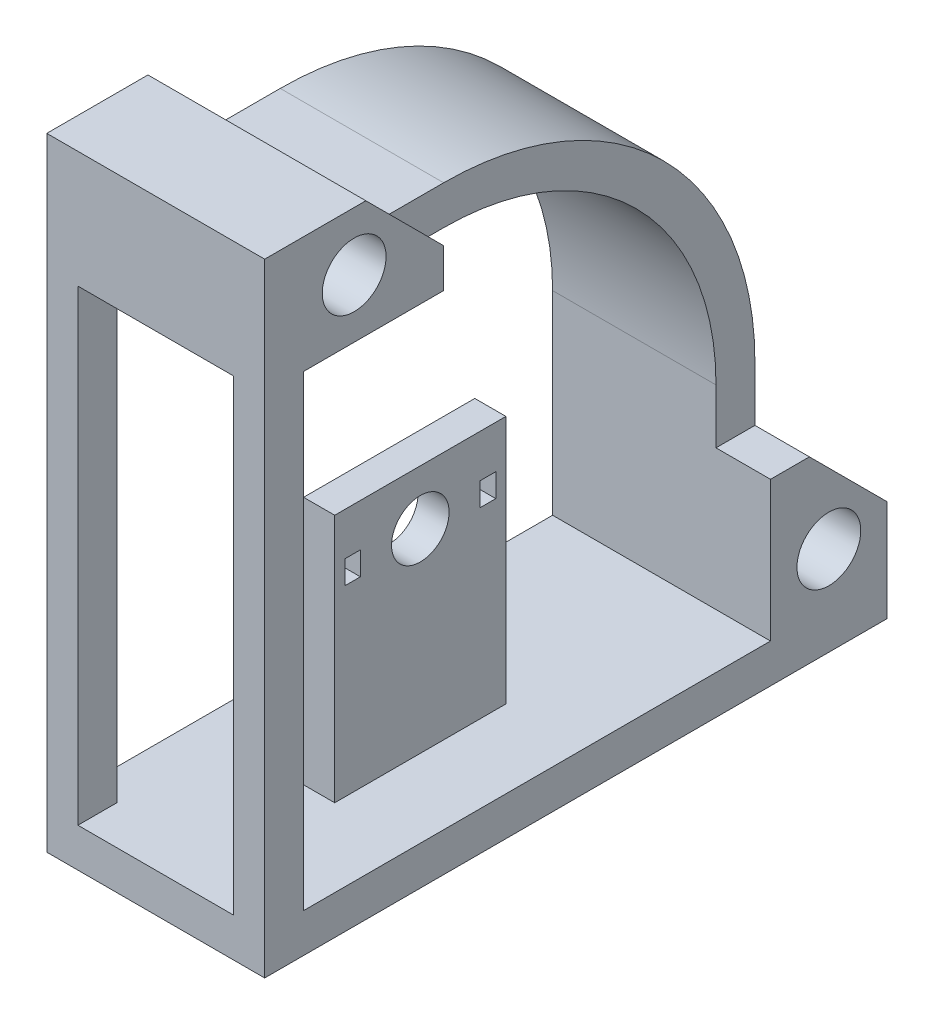
SolidWorks part; units mm, degrees
ref_plane "Спереди" through (0, 0, 0) normal (0, 0, 1) x (1, 0, 0)
ref_plane "Сверху" through (0, 0, 0) normal (0, 1, 0) x (1, 0, 0)
ref_plane "Справа" through (0, 0, 0) normal (1, 0, 0) x (0, 0, -1)
sketch "Sketch2" plane through (0, 0, 0) normal (1, 0, 0) x (0, 0, -1)
  line L0 (0, 40) -> (0, 0) construction
  line L1 (0, 0) -> (40, 0) construction
  line L2 (0, 40) -> (-30, 40)
  line L3 (40, -30) -> (-30, -30)
  line L4 (-25, 35) -> (-25, -25)
  line L5 (40, -30) -> (40, 0)
  line L6 (-30, -30) -> (-30, 40)
  line L7 (-25, -25) -> (35, -25)
  line L8 (35, -25) -> (35, 0)
  line L9 (-25, 35) -> (0, 35)
  line L10 (24.7487, 24.7487) -> (28.2843, 28.2843) construction
  line L12 (-25, 35) -> (-30, 35) construction
  line L13 (-25, -25) -> (-25, -30) construction
  arc A0 (0, 40) -> (40, 0) centre (0, 0) cw
  arc A1 (0, 35) -> (35, 0) centre (0, 0) cw
  dimension "D1" = 40
  dimension "D3" = 5
  dimension "D2" = 70
extrude "Boss-Extrude1" add sketch "Sketch2" along normal blind 28
sketch "Sketch3" plane through (28, 0, 0) normal (1, 0, 0) x (0, 0, -1)
  line L0 (-11, -25) -> (-11, 7)
  line L1 (-25, -25) -> (35, -25) construction
  line L2 (-11, 7) -> (11, 7)
  line L3 (11, 7) -> (11, -25)
  line L4 (11, -25) -> (-11, -25)
  line L5 (0, 7) -> (0, -25) construction
  line L6 (8.7, 0) -> (-8.7, 0) construction
  line L7 (7.7, 0) -> (3.7, 0) construction
  line L8 (-9.7, -1.5) -> (-7.7, -1.5)
  line L9 (-9.7, -1.5) -> (-9.7, 1.5)
  line L10 (-9.7, 1.5) -> (-7.7, 1.5)
  line L11 (-7.7, -1.5) -> (-7.7, 1.5)
  line L12 (-9.7, -1.5) -> (-7.7, 1.5) construction
  line L13 (-9.7, 1.5) -> (-7.7, -1.5) construction
  line L14 (9.7, -1.5) -> (7.7, -1.5)
  line L15 (9.7, -1.5) -> (9.7, 1.5)
  line L16 (9.7, 1.5) -> (7.7, 1.5)
  line L17 (7.7, -1.5) -> (7.7, 1.5)
  line L18 (9.7, -1.5) -> (7.7, 1.5) construction
  line L19 (9.7, 1.5) -> (7.7, -1.5) construction
  circle A3 centre (0, 0) radius 3.7
  point P18 (0, 0)
  dimension "D1" = 7.4
  dimension "D2" = 22
  dimension "D3" = 7
  dimension "D4" = 2
  dimension "D5" = 3
  dimension "D6" = 4
extrude "Boss-Extrude2" add sketch "Sketch3" against normal blind 4 from offset 10 offset against normal yes
sketch "Sketch4" plane through (28, 0, 0) normal (1, 0, 0) x (0, 0, -1)
  line L0 (0, 40) -> (-7, 40)
  line L1 (0, 40) -> (-30, 40) construction
  line L2 (-7, 40) -> (-7, 35)
  line L3 (0, 35) -> (-25, 35) construction
  line L4 (-7, 35) -> (0, 35)
  line L5 (35, -7) -> (40, -7)
  line L6 (35, -25) -> (35, 0) construction
  line L7 (40, -30) -> (40, 0) construction
  line L8 (40, -7) -> (40, 0)
  line L9 (35, 0) -> (35, -7)
  arc A0 (0, 40) -> (40, 0) centre (0, 0) cw
  arc A1 (35, 0) -> (0, 35) centre (0, 0) ccw
  arc A3 (40, 0) -> (0, 40) centre (0, 0) ccw construction
  dimension "D1" = 7
  dimension "D2" = 7
extrude "Cut-Extrude1" cut sketch "Sketch4" against normal blind 7
chamfer "Chamfer1" distance 10 angle 30 1 edges at (14, -25, 0)
sketch "Sketch5" plane through (0, 0, 30) normal (0, 0, 1) x (1, 0, 0)
  line L0 (14, 40) -> (14, -30) construction
  line L1 (28, 40) -> (0, 40) construction
  line L2 (28, -30) -> (0, -30) construction
  line L4 (24, -25) -> (4, -25)
  line L5 (24, -25) -> (24, 35)
  line L6 (24, 35) -> (4, 35)
  line L7 (4, -25) -> (4, 35)
  line L8 (24, -25) -> (4, 35) construction
  line L9 (24, 35) -> (4, -25) construction
  point P6 (14, 5)
  point P11 (0, 0)
  dimension "D1" = 20
  dimension "D2" = 60
extrude "Cut-Extrude2" cut sketch "Sketch5" against normal up to next
sketch "Sketch6" plane through (28, 0, 0) normal (1, 0, 0) x (0, 0, -1)
  line L0 (-7, 40) -> (-30, 40)
  line L1 (40, -7) -> (40, -30)
  line L2 (-30, 40) -> (-30, 50)
  line L3 (-30, 50) -> (-7, 50)
  line L4 (-7, 50) -> (-7, 40)
  line L5 (40, -7) -> (50, -7)
  line L6 (50, -7) -> (50, -30)
  line L7 (50, -30) -> (40, -30)
  dimension "D1" = 10
extrude "Boss-Extrude3" add sketch "Sketch6" against normal up to surface (28 mm away) up to face at (0, 5.6569, -5.6569)
sketch "Sketch8" plane through (28, 0, 0) normal (1, 0, 0) x (0, 0, -1)
  line L0 (-30, 42.5) -> (-7, 42.5) construction
  line L1 (-30, 50) -> (-30, -30) construction
  line L2 (-7, 50) -> (-7, 35) construction
  line L3 (42.5, -7) -> (42.5, -30) construction
  line L4 (35, -7) -> (50, -7) construction
  line L5 (-30, -30) -> (50, -30) construction
  circle A0 centre (-18.5, 42.5) radius 4.1
  circle A1 centre (42.5, -18.5) radius 4.1
  point P16 (-7, 42.5)
  dimension "D1" = 8.2
extrude "Cut-Extrude3" cut sketch "Sketch8" against normal through all
chamfer "Chamfer2" distance 10 angle 45 2 edges at (14, -7, -50) (14, 50, 7)
